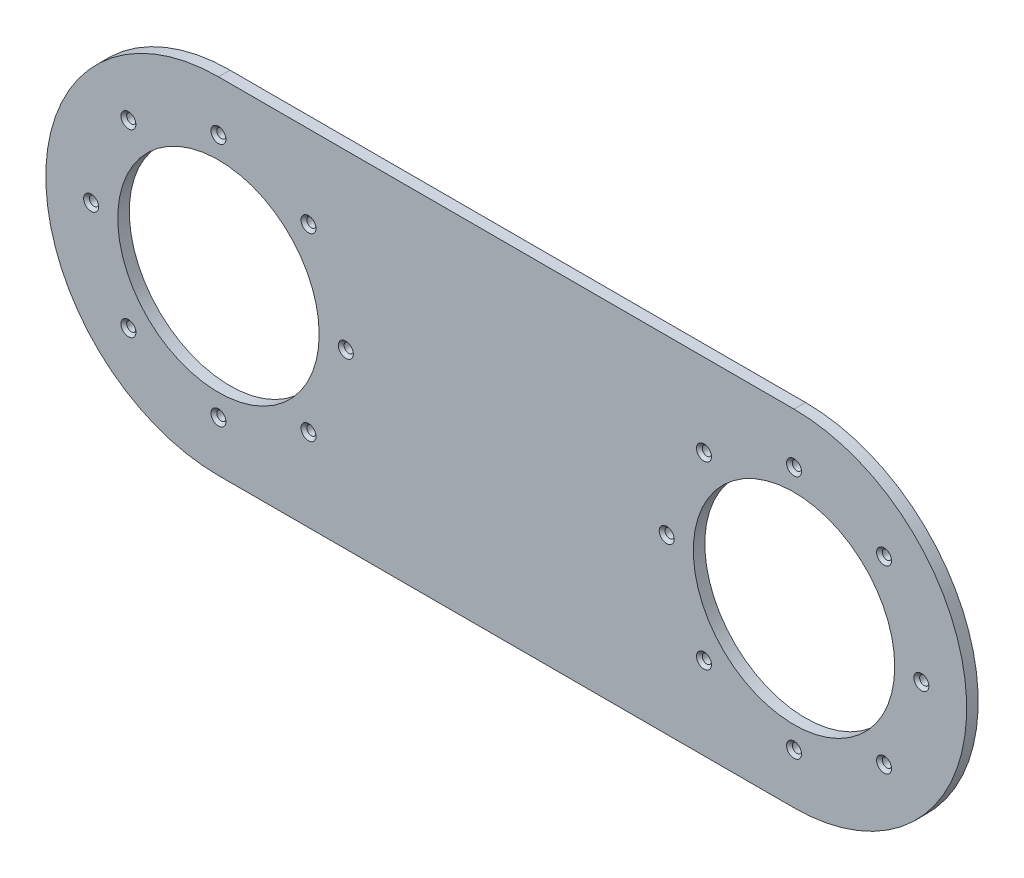
SolidWorks part; units mm, degrees
ref_plane "前视基准面" through (0, 0, 0) normal (0, 0, 1) x (1, 0, 0)
ref_plane "上视基准面" through (0, 0, 0) normal (0, 1, 0) x (1, 0, 0)
ref_plane "右视基准面" through (0, 0, 0) normal (1, 0, 0) x (0, 0, -1)
other "Configuration Table"
sketch "草图1" plane through (0, 0, 0) normal (0, 0, 1) x (1, 0, 0)
  line L0 (0, 0) -> (200, 0) construction
  line L1 (0, 60) -> (200, 60)
  line L2 (0, -60) -> (200, -60)
  arc A0 (0, 60) -> (0, -60) centre (0, 0) ccw
  arc A1 (200, -60) -> (200, 60) centre (200, 0) ccw
  circle A2 centre (0, 0) radius 35
  circle A3 centre (200, 0) radius 35
  point P3 (100, 0)
  point P12 (0, 0)
  point P13 (0, 0)
  point P14 (0, 0)
  point P15 (0, 0)
  dimension "D2" = 60
  dimension "D3" = 70
  dimension "D4" = 70
  dimension "D1" = 200
extrude "凸台-拉伸1" add sketch "草图1" along normal blind 4
sketch "草图2" plane through (0, 0, 4) normal (0, 0, 1) x (1, 0, 0)
  line L0 (100, 60) -> (100, -60) construction
  line L2 (0, -60) -> (200, -60)
  line L3 (200, 60) -> (0, 60)
  line L4 (0, -60) -> (200, -60)
  line L5 (200, 60) -> (0, 60)
  circle A0 centre (0, 42.5) radius 1.6
  circle A1 centre (0, -42.5) radius 1.6
  arc A2 (0, 60) -> (0, -60) centre (0, 0) ccw
  arc A3 (200, -60) -> (200, 60) centre (200, 0) ccw
  arc A4 (0, 60) -> (0, -60) centre (0, 0) ccw
  arc A5 (200, -60) -> (200, 60) centre (200, 0) ccw
  circle A6 centre (44.25, 0) radius 1.6
  circle A7 centre (31.2895, -31.2895) radius 1.6
  circle A8 centre (0, -44.25) radius 1.6
  circle A9 centre (-31.2895, -31.2895) radius 1.6
  circle A10 centre (-44.25, 0) radius 1.6
  circle A11 centre (-31.2895, 31.2895) radius 1.6
  circle A12 centre (0, 44.25) radius 1.6
  circle A13 centre (31.2895, 31.2895) radius 1.6
  circle A14 centre (168.7105, -31.2895) radius 1.6
  circle A15 centre (231.2895, -31.2895) radius 1.6
  circle A16 centre (200, -42.5) radius 1.6
  circle A17 centre (155.75, 0) radius 1.6
  circle A18 centre (244.25, 0) radius 1.6
  circle A19 centre (168.7105, 31.2895) radius 1.6
  circle A20 centre (200, 42.5) radius 1.6
  circle A21 centre (231.2895, 31.2895) radius 1.6
  point P28 (0, 0)
  dimension "D2" = 3.2
  dimension "D3" = 3.2
  dimension "D6" = 3.2
  dimension "D4" = 42.5
  dimension "D5" = 42.5
  dimension "D7" = 44.25
  dimension "D1" = 0
  dimension "D8" = 8
extrude "切除-拉伸1" cut sketch "草图2" against normal blind 5 contours A11 | A10 | A9 | A13 | A12 A0 | A0 A12 | A19 | A17 | A14 | A16 | A15 | A18 | A21 | A20 | A1 | A7 | A6
chamfer "倒角1" distance 1 angle 45 16 edges at (245.85, 0, 4) (232.8895, 31.2895, 4) (201.6, 42.5, 4) (232.8895, -31.2895, 4) (201.6, -42.5, 4) (170.3105, 31.2895, 4) (170.3105, -31.2895, 4) (157.35, 0, 4) (32.8895, 31.2895, 4) (45.85, 0, 4) (32.8895, -31.2895, 4) (1.6, -42.5, 4) (-29.6895, -31.2895, 4) (1.6, 42.5, 4) (-42.65, 0, 4) (-29.6895, 31.2895, 4)
